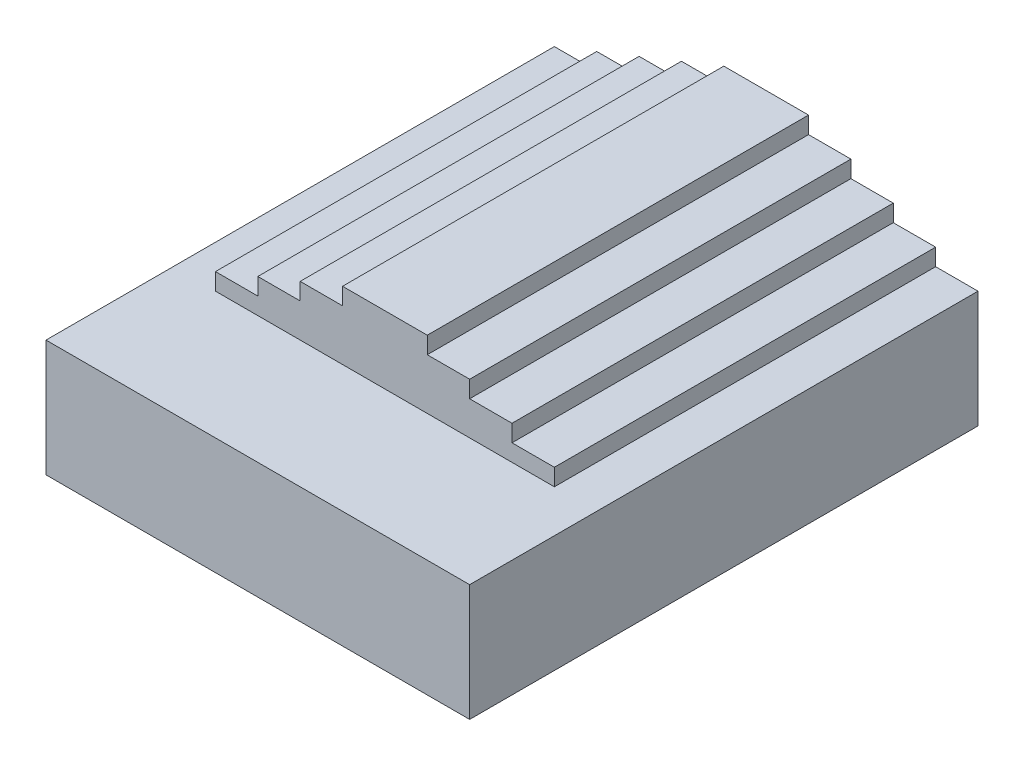
SolidWorks part; units mm, degrees
ref_plane "前视基准面" through (0, 0, 0) normal (0, 0, 1) x (1, 0, 0)
ref_plane "上视基准面" through (0, 0, 0) normal (0, 1, 0) x (1, 0, 0)
ref_plane "右视基准面" through (0, 0, 0) normal (1, 0, 0) x (0, 0, -1)
sketch "草图1" plane through (0, 0, 0) normal (0, 0, 1) x (1, 0, 0)
  line L0 (-37.0176, 4) -> (-27.0176, 4)
  line L1 (-57.0176, -6) -> (-57.0176, -17.7763)
  line L2 (-12.0176, -4) -> (-12.0176, -2)
  line L3 (-12.0176, -2) -> (-17.0176, -2)
  line L4 (-17.0176, -2) -> (-17.0176, 0)
  line L5 (-17.0176, 0) -> (-22.0176, 0)
  line L6 (-22.0176, 0) -> (-22.0176, 2)
  line L7 (-22.0176, 2) -> (-27.0176, 2)
  line L8 (-27.0176, 2) -> (-27.0176, 4)
  line L9 (-32.0176, 36.9402) -> (-32.0176, -40.9683) construction
  line L10 (-57.0176, -4) -> (-52.0176, -4)
  line L11 (-57.0176, -6) -> (-57.0176, -4)
  line L12 (-37.0176, 2) -> (-37.0176, 4)
  line L13 (-42.0176, 2) -> (-37.0176, 2)
  line L14 (-42.0176, 0) -> (-42.0176, 2)
  line L15 (-47.0176, 0) -> (-42.0176, 0)
  line L16 (-47.0176, -2) -> (-47.0176, 0)
  line L17 (-52.0176, -2) -> (-47.0176, -2)
  line L18 (-7.0176, -6) -> (-7.0176, -4)
  line L19 (-7.0176, -4) -> (-12.0176, -4)
  line L20 (-52.0176, -4) -> (-52.0176, -2)
  line L21 (-57.0176, -17.7763) -> (-7.0176, -17.7763)
  line L22 (-7.0176, -17.7763) -> (-7.0176, -6)
  point P2 (-32.0176, 4)
  point P18 (-32.0176, 4)
  point P25 (-32.0176, -6)
  point P27 (-32.0176, -6)
  dimension "D1" = 2
  dimension "D2" = 2
  dimension "D3" = 2
  dimension "D4" = 2
  dimension "D5" = 2
  dimension "D6" = 10
  dimension "D7" = 5
  dimension "D8" = 5
  dimension "D9" = 5
  dimension "D10" = 5
  dimension "D11" = 50
extrude "凸台-拉伸1" add sketch "草图1" along normal blind 60
sketch "草图3" plane through (-7.0176, 0, 0) normal (1, 0, 0) x (0, 0, -1)
  line L0 (-45, 4) -> (-45, -4)
  line L1 (-60, 4) -> (0, 4) construction
  line L2 (-60, -4) -> (0, -4) construction
  line L3 (-45, -4) -> (-60, -4)
  line L4 (-60, -4) -> (-60, 4)
  line L5 (-60, 4) -> (-45, 4)
  dimension "D1" = 15
extrude "切除-拉伸1" cut sketch "草图3" against normal blind 50
